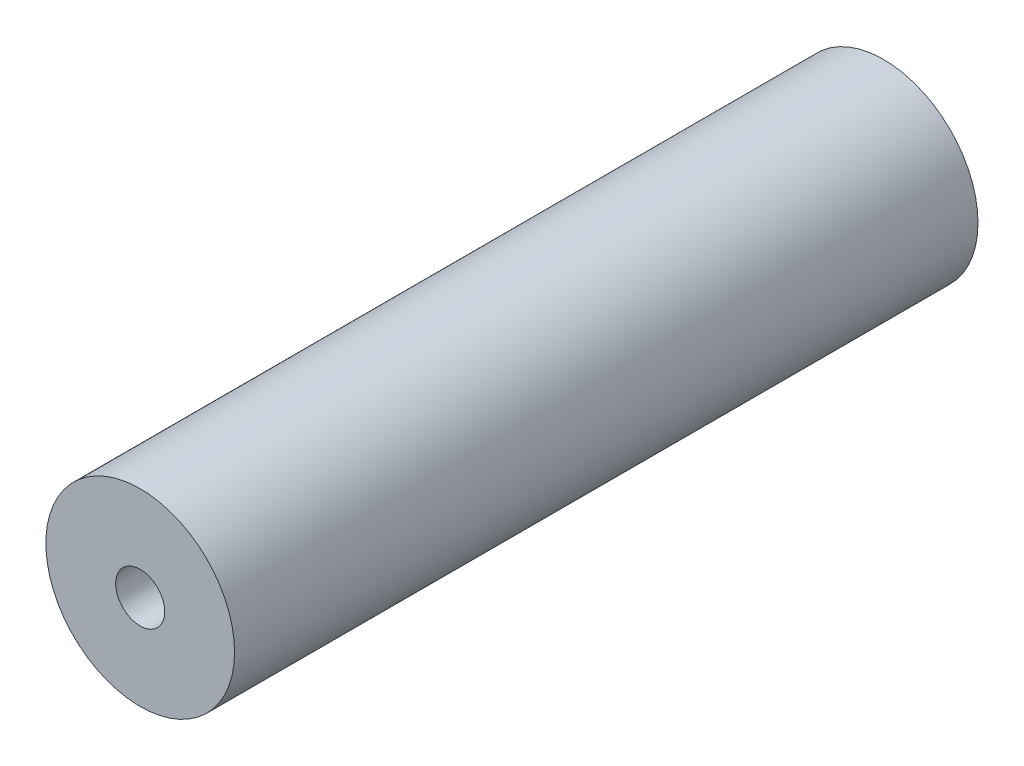
SolidWorks part; units mm, degrees
material "1060 合金"
ref_plane "正面" through (0, 0, 0) normal (0, 0, 1) x (1, 0, 0)
ref_plane "平面" through (0, 0, 0) normal (0, 1, 0) x (1, 0, 0)
ref_plane "右側面" through (0, 0, 0) normal (1, 0, 0) x (0, 0, -1)
sketch "ｽｹｯﾁ1" plane through (0, 0, 0) normal (0, 0, 1) x (1, 0, 0)
  circle A0 centre (0, 0) radius 5
  circle A1 centre (0, 0) radius 1.3
  dimension "D1" = 10
  dimension "D2" = 2.6
extrude "ﾎﾞｽ - 押し出し2" add sketch "ｽｹｯﾁ1" along normal blind 39.4
